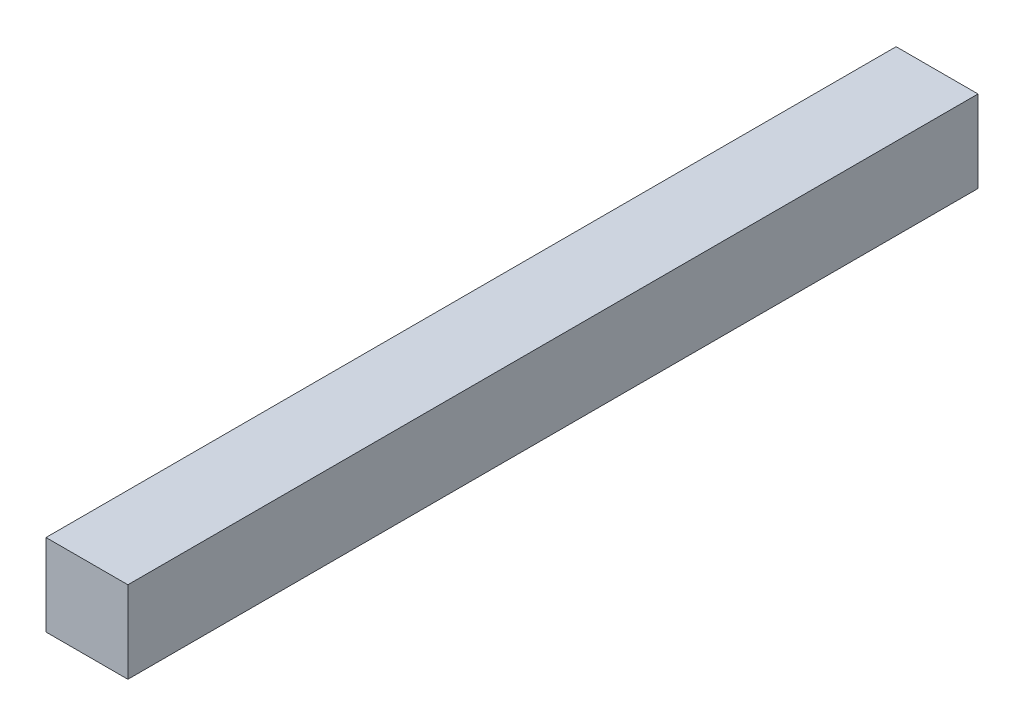
SolidWorks part; units mm, degrees
ref_plane "Front Plane" through (0, 0, 0) normal (1, 0, 0) x (0, 1, 0)
ref_plane "Top Plane" through (0, 0, 0) normal (0, 0, 1) x (0, 1, 0)
ref_plane "Right Plane" through (0, 0, 0) normal (0, 1, 0) x (-1, 0, 0)
sketch "Sketch1" plane through (0, 0, 0) normal (0, 0, 1) x (0, 1, 0)
  line L1 (0, 0) -> (36.7, 0)
  line L2 (0, 0) -> (0, 36.7)
  line L3 (0, 36.7) -> (36.7, 36.7)
  line L4 (36.7, 0) -> (36.7, 36.7)
  dimension "D1" = 36.7
  dimension "D2" = 36.7
extrude "Boss-Extrude1" add sketch "Sketch1" along normal blind 381
